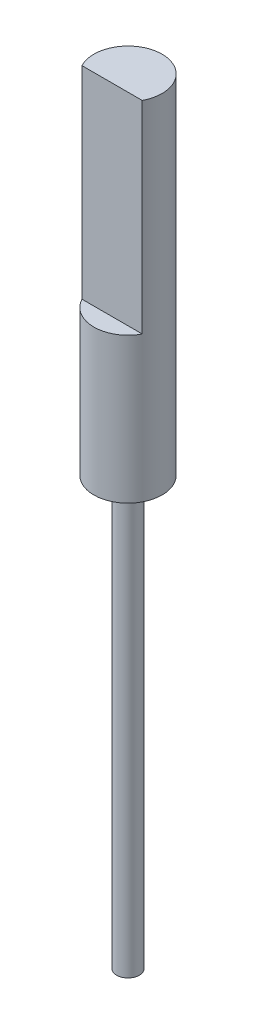
SolidWorks part; units mm, degrees
material "A286 Súper aleación a base de hierro"
ref_plane "Alzado" through (0, 0, 0) normal (0, 0, 1) x (1, 0, 0)
ref_plane "Planta" through (0, 0, 0) normal (0, 1, 0) x (1, 0, 0)
ref_plane "Vista lateral" through (0, 0, 0) normal (1, 0, 0) x (0, 0, -1)
sketch "Croquis1" plane through (0, 0, 0) normal (0, 1, 0) x (1, 0, 0)
  circle A0 centre (0, 0) radius 0.5
  dimension "D1" = 1
extrude "Saliente-Extruir1" add sketch "Croquis1" along normal blind 18.8
sketch "Croquis2" plane through (0, 18.8, 0) normal (0, 1, 0) x (1, 0, 0)
  circle A0 centre (0, 0) radius 1.5
  dimension "D1" = 3
extrude "Saliente-Extruir2" add sketch "Croquis2" along normal blind 15.3
sketch "Croquis3" plane through (0, 34.1, 0) normal (0, 1, 0) x (1, 0, 0)
  line L3 (-1.3266, -0.7) -> (1.3266, -0.7)
  circle A0 centre (0, 0) radius 1.5 construction
  arc A3 (-1.3266, -0.7) -> (1.3266, -0.7) centre (0, 0) ccw
  point P1 (0, 0)
  point P4 (0, 0)
  point P6 (0, 0)
  point P7 (0, 0)
  point P8 (0, 0)
  point P9 (0, 0)
  dimension "D1" = 0.7
extrude "Cortar-Extruir1" cut sketch "Croquis3" against normal blind 8.9
